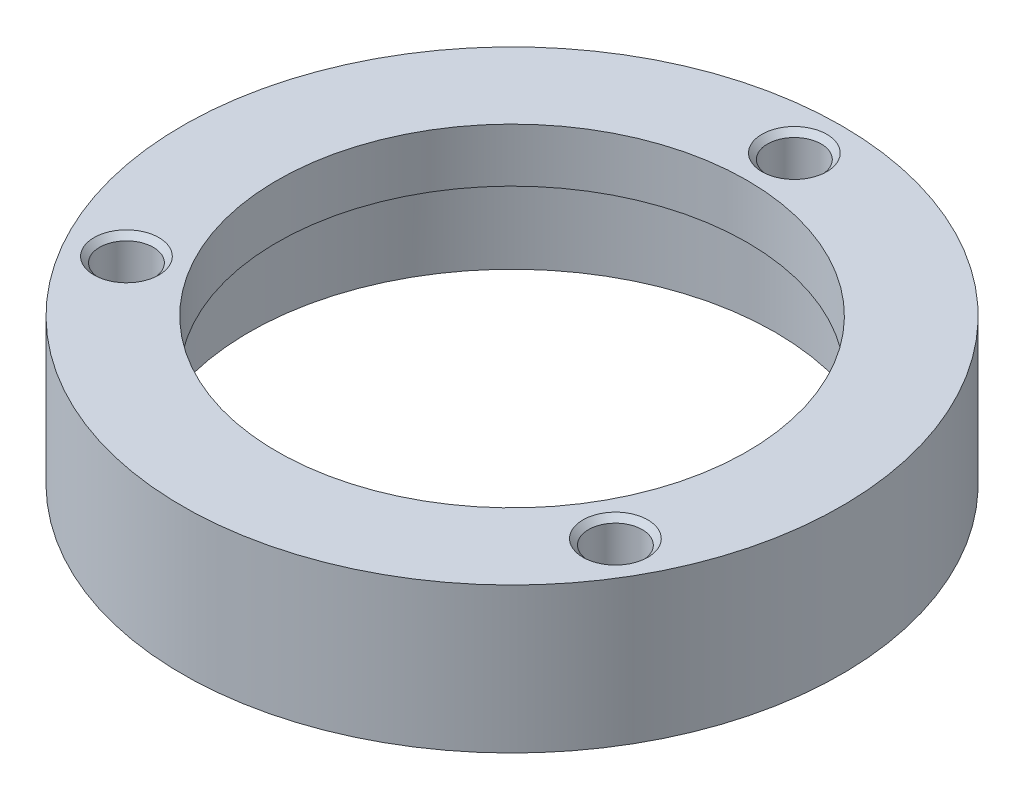
SolidWorks part; units mm, degrees
ref_plane "Front Plane" through (0, 0, 0) normal (0, 0, 1) x (1, 0, 0)
ref_plane "Top Plane" through (0, 0, 0) normal (0, 1, 0) x (1, 0, 0)
ref_plane "Right Plane" through (0, 0, 0) normal (1, 0, 0) x (0, 0, -1)
sketch "Sketch1" plane through (0, 0, 0) normal (0, 1, 0) x (1, 0, 0)
  circle A0 centre (0, 0) radius 21
  circle A1 centre (0, 0) radius 29.45
  circle A2 centre (0, 0) radius 29.25 construction
  dimension "D1" = 0.2
  dimension "D2" = 42
  dimension "D3" = 58.9
extrude "Boss-Extrude1" add sketch "Sketch1" along normal blind 13
sketch "Sketch2" plane through (0, 13, 0) normal (0, 1, 0) x (1, 0, 0)
  line L0 (0, 0) -> (0, 21) construction
  line L1 (0, 21) -> (0, 29.45) construction
  circle A0 centre (0, 25.225) radius 2.4
  circle A1 centre (0, 0) radius 21 construction
  circle A2 centre (0, 0) radius 29.45 construction
  circle A3 centre (21.8455, -12.6125) radius 2.4
  circle A4 centre (-21.8455, -12.6125) radius 2.4
  point P19 (0, 0)
  dimension "D2" = 4.8
  dimension "D1" = 25.225
  dimension "D3" = 3
extrude "Cut-Extrude1" cut sketch "Sketch2" against normal blind 4
chamfer "Chamfer1" distance 0.5 angle 45 3 edges at (-21.8455, 13, 15.0125) (21.8455, 13, 15.0125) (0, 13, -22.825)
sketch "Sketch4" plane through (0, 0, 0) normal (0, -1, 0) x (1, 0, 0)
  circle A0 centre (0, 0) radius 23.5
  dimension "D1" = 47
extrude "Cut-Extrude2" cut sketch "Sketch4" against normal offset from surface (8.2 mm away) 4.8 up to face at (-21.8455, 13, 15.5125)
